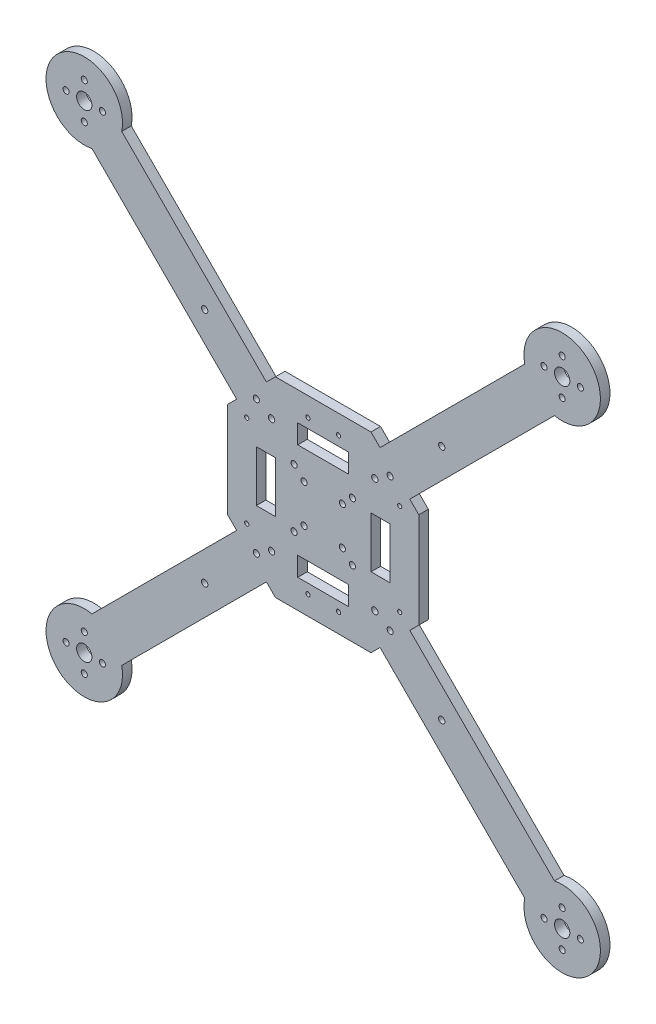
SolidWorks part; units mm, degrees
material "碳纤维板_1600kg_m3"
ref_plane "前视基准面" through (0, 0, 0) normal (0, 0, 1) x (1, 0, 0)
ref_plane "上视基准面" through (0, 0, 0) normal (0, 1, 0) x (1, 0, 0)
ref_plane "右视基准面" through (0, 0, 0) normal (1, 0, 0) x (0, 0, -1)
other "Configuration Table"
sketch "草图1" plane through (0, 0, 0) normal (0, 0, 1) x (1, 0, 0)
  line L0 (50, 25) -> (25, 50)
  line L1 (25, 50) -> (-25, 50)
  line L2 (-25, 50) -> (-50, 25)
  line L3 (-50, 25) -> (-50, -25)
  line L4 (-50, -25) -> (-25, -50)
  line L5 (-25, -50) -> (25, -50)
  line L6 (25, -50) -> (50, -25)
  line L7 (50, -25) -> (50, 25)
extrude "中心八边形" add sketch "草图1" along normal blind 5
sketch "草图2" plane through (0, 0, 0) normal (0, 0, 1) x (1, 0, 0)
  line L0 (14.8492, 30.4056) -> (120.0503, 135.6066)
  line L1 (120.0503, 135.6066) -> (135.6066, 120.0503)
  line L2 (135.6066, 120.0503) -> (30.4056, 14.8492)
  line L3 (30.4056, 14.8492) -> (14.8492, 30.4056)
  line L4 (-30.4056, 14.8492) -> (-135.6066, 120.0503)
  line L5 (-135.6066, 120.0503) -> (-120.0503, 135.6066)
  line L6 (-120.0503, 135.6066) -> (-14.8492, 30.4056)
  line L7 (-14.8492, 30.4056) -> (-30.4056, 14.8492)
  line L8 (-14.8492, -30.4056) -> (-120.0503, -135.6066)
  line L9 (-120.0503, -135.6066) -> (-135.6066, -120.0503)
  line L10 (-135.6066, -120.0503) -> (-30.4056, -14.8492)
  line L11 (-30.4056, -14.8492) -> (-14.8492, -30.4056)
  line L12 (30.4056, -14.8492) -> (135.6066, -120.0503)
  line L13 (135.6066, -120.0503) -> (120.0503, -135.6066)
  line L14 (120.0503, -135.6066) -> (14.8492, -30.4056)
  line L15 (14.8492, -30.4056) -> (30.4056, -14.8492)
extrude "四机臂" add sketch "草图2" along normal blind 5
sketch "草图3" plane through (0, 0, 0) normal (0, 0, 1) x (1, 0, 0)
  circle A0 centre (-125, -125) radius 20
  circle A1 centre (-125, 125) radius 20
  circle A2 centre (125, -125) radius 20
  circle A3 centre (125, 125) radius 20
extrude "电机端台" add sketch "草图3" along normal blind 5
sketch "草图4" plane through (0, 0, 0) normal (0, 0, 1) x (1, 0, 0)
  circle A4 centre (-125, -125) radius 4
  circle A5 centre (-35, -35) radius 1.6
  circle A6 centre (-8, -40) radius 1.1
  circle A11 centre (-125, 125) radius 4
  circle A12 centre (-35, 35) radius 1.6
  circle A13 centre (-8, 40) radius 1.1
  circle A18 centre (125, -125) radius 4
  circle A19 centre (35, -35) radius 1.6
  circle A20 centre (8, -40) radius 1.1
  circle A25 centre (125, 125) radius 4
  circle A26 centre (35, 35) radius 1.6
  circle A27 centre (8, 40) radius 1.1
  circle A28 centre (-15.25, -15.25) radius 1.6
  circle A29 centre (-15.25, 15.25) radius 1.6
  circle A30 centre (15.25, -15.25) radius 1.6
  circle A31 centre (15.25, 15.25) radius 1.6
  circle A32 centre (-10, -10) radius 1.6
  circle A33 centre (-10, 10) radius 1.6
  circle A34 centre (10, -10) radius 1.6
  circle A35 centre (10, 10) radius 1.6
  circle A36 centre (-134.5, -125) radius 1.6
  circle A37 centre (-125, -134.5) radius 1.6
  circle A38 centre (-115.5, -125) radius 1.6
  circle A39 centre (-125, -115.5) radius 1.6
  circle A40 centre (-134.5, 125) radius 1.6
  circle A41 centre (-125, 115.5) radius 1.6
  circle A42 centre (-115.5, 125) radius 1.6
  circle A43 centre (-125, 134.5) radius 1.6
  circle A44 centre (115.5, -125) radius 1.6
  circle A45 centre (125, -134.5) radius 1.6
  circle A46 centre (134.5, -125) radius 1.6
  circle A47 centre (125, -115.5) radius 1.6
  circle A48 centre (115.5, 125) radius 1.6
  circle A49 centre (125, 115.5) radius 1.6
  circle A50 centre (134.5, 125) radius 1.6
  circle A51 centre (125, 134.5) radius 1.6
extrude "电机_支柱_飞控_四个钢索孔" cut sketch "草图4" along normal blind 5
sketch "草图5" plane through (0, 0, 0) normal (0, 0, 1) x (1, 0, 0)
  circle A0 centre (-40, -24) radius 1.1
  circle A1 centre (-40, 24) radius 1.1
  circle A2 centre (40, -24) radius 1.1
  circle A3 centre (40, 24) radius 1.1
extrude "左右摄像头钢索孔" cut sketch "草图5" along normal blind 5
sketch "草图7" plane through (0, 0, 0) normal (0, 0, 1) x (1, 0, 0)
  circle A12 centre (-62, -62) radius 1.65
  circle A13 centre (-62, 62) radius 1.65
  circle A14 centre (62, -62) radius 1.65
  circle A15 centre (62, 62) radius 1.65
extrude "托板机臂中线四孔_M3" cut sketch "草图7" along normal blind 5
sketch "草图8" plane through (0, 0, 0) normal (0, 0, 1) x (1, 0, 0)
  circle A12 centre (-27, -30) radius 1.65
  circle A13 centre (-27, 30) radius 1.65
  circle A14 centre (27, -30) radius 1.65
  circle A15 centre (27, 30) radius 1.65
extrude "Pixhawk托板支柱四孔_M3_54x60" cut sketch "草图8" along normal blind 5
sketch "草图9" plane through (0, 0, 0) normal (0, 0, 1) x (1, 0, 0)
  line L0 (-35, 35) -> (35, -35) construction
  line L1 (35, 35) -> (-35, -35) construction
  line L2 (0, 0) -> (-50, 0) construction
  line L3 (-50, 25) -> (-50, -25) construction
  line L4 (-35, -13.341) -> (-25, -13.341)
  line L5 (-35, 13.341) -> (-25, 13.341)
  line L6 (-35, 13.341) -> (-35, -13.341)
  line L8 (-25, 13.341) -> (-25, -13.341)
  line L9 (13.341, -25) -> (-13.341, -25)
  line L10 (13.341, -35) -> (-13.341, -35)
  line L11 (13.341, -35) -> (13.341, -25)
  line L12 (-13.341, -35) -> (-13.341, -25)
  line L13 (35, 13.341) -> (25, 13.341)
  line L14 (35, -13.341) -> (25, -13.341)
  line L15 (35, -13.341) -> (35, 13.341)
  line L16 (25, -13.341) -> (25, 13.341)
  line L17 (-13.341, 35) -> (13.341, 35)
  line L18 (-13.341, 25) -> (13.341, 25)
  line L19 (13.341, 35) -> (13.341, 25)
  line L20 (-13.341, 35) -> (-13.341, 25)
  dimension "D1" = 10
extrude "飞控至电调矩形走线孔_20x12" cut sketch "草图9" along normal blind 5
